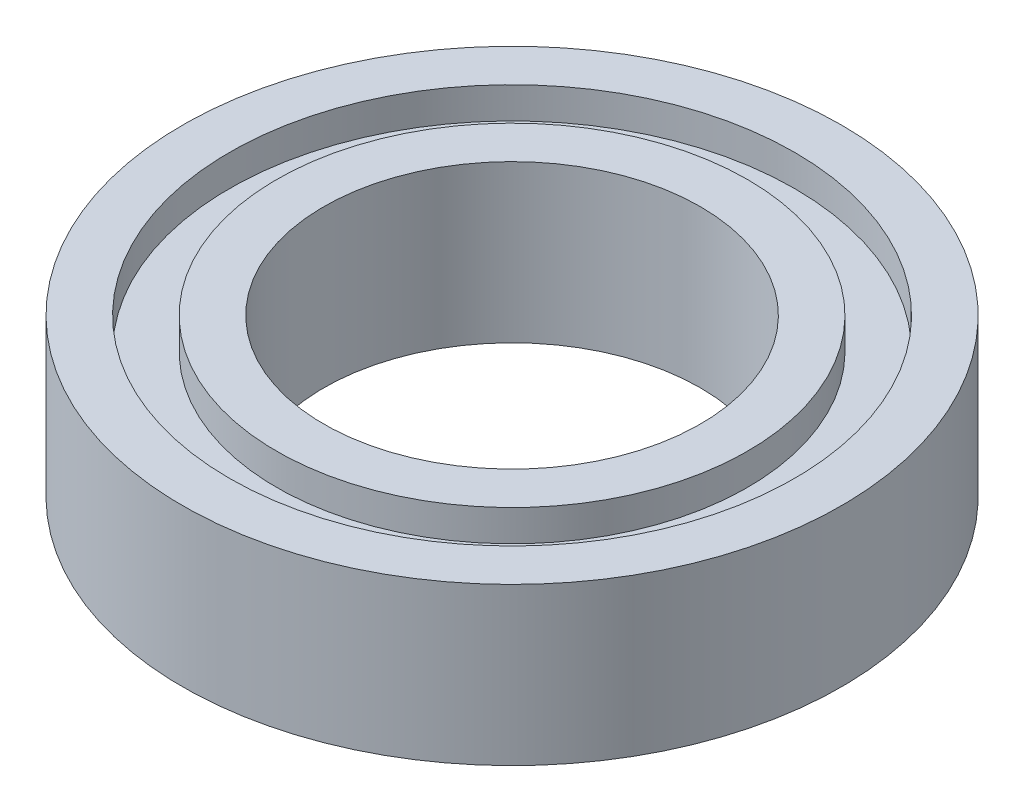
SolidWorks part; units mm, degrees
ref_plane "Alzado" through (0, 0, 0) normal (0, 0, 1) x (1, 0, 0)
ref_plane "Planta" through (0, 0, 0) normal (0, 1, 0) x (1, 0, 0)
ref_plane "Vista lateral" through (0, 0, 0) normal (1, 0, 0) x (0, 0, -1)
sketch "Croquis1" plane through (0, 0, 0) normal (0, 0, 1) x (1, 0, 0)
  line L0 (0, 0) -> (0, 16.452) construction
  line L1 (-6, 6.8567) -> (-6, 11.8567)
  line L2 (-6, 11.8567) -> (-7.5, 11.8567)
  line L3 (-7.5, 11.8567) -> (-7.5, 10.8567)
  line L4 (-7.5, 10.8567) -> (-9, 10.8567)
  line L5 (-9, 10.8567) -> (-9, 11.8567)
  line L6 (-9, 11.8567) -> (-10.5, 11.8567)
  line L7 (-10.5, 11.8567) -> (-10.5, 6.8567)
  line L8 (-10.5, 6.8567) -> (-9, 6.8567)
  line L9 (-9, 6.8567) -> (-9, 7.8567)
  line L10 (-9, 7.8567) -> (-7.5, 7.8567)
  line L11 (-7.5, 7.8567) -> (-7.5, 6.8567)
  line L12 (-7.5, 6.8567) -> (-6, 6.8567)
  dimension "D1" = 10.5
  dimension "D2" = 1.5
  dimension "D3" = 1
  dimension "D4" = 1
  dimension "D5" = 5
  dimension "D6" = 6
revolve "Revolución1" add sketch "Croquis1" angle 360 about L0
